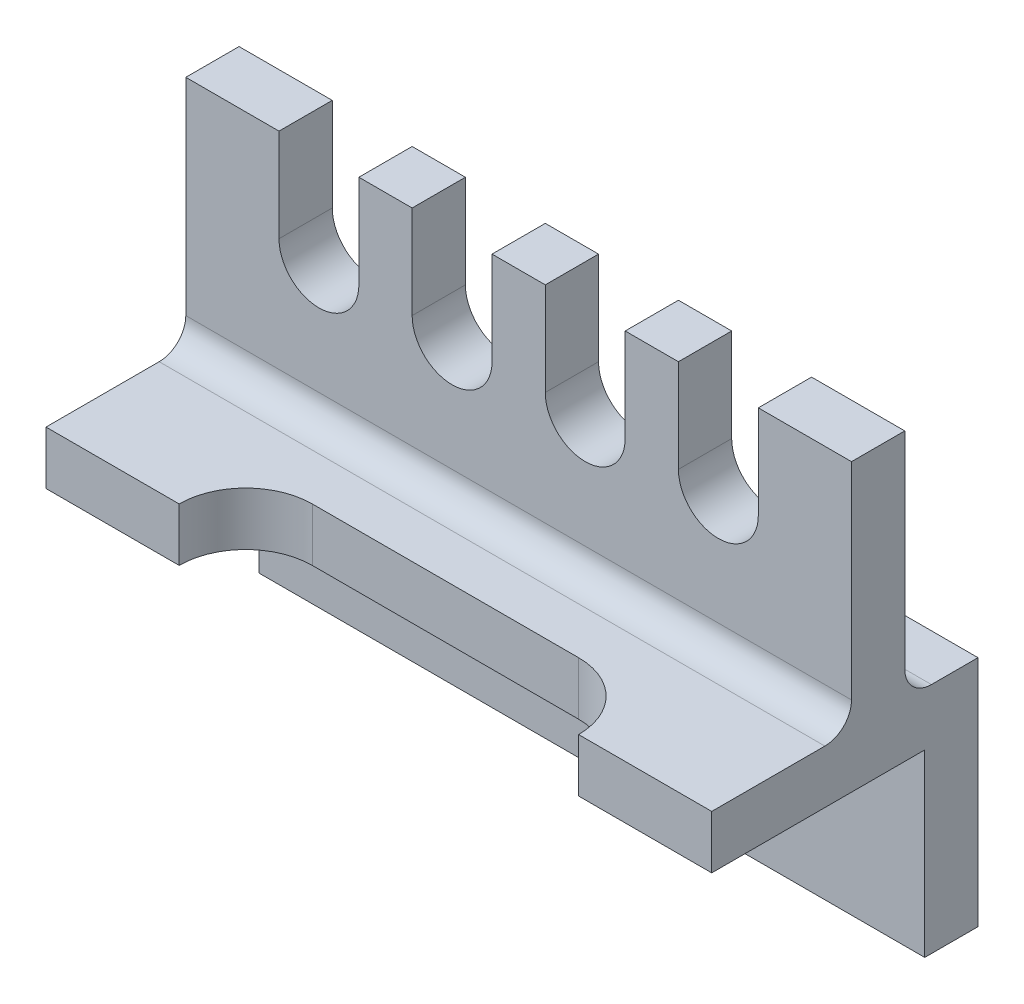
SolidWorks part; units mm, degrees
ref_plane "Front Plane" through (0, 0, 0) normal (0, 0, 1) x (1, 0, 0)
ref_plane "Top Plane" through (0, 0, 0) normal (0, 1, 0) x (1, 0, 0)
ref_plane "Right Plane" through (0, 0, 0) normal (1, 0, 0) x (0, 0, -1)
sketch "Sketch1" plane through (0, 0, 0) normal (1, 0, 0) x (0, 0, -1)
  line L0 (-19, 70) -> (-11, 70)
  line L1 (-11, 70) -> (-11, 39)
  line L2 (-7, 35) -> (0, 35)
  line L3 (0, 35) -> (0, 0)
  line L4 (0, 0) -> (-8, 0)
  line L5 (-8, 0) -> (-8, 27)
  line L6 (-8, 27) -> (-40, 27)
  line L7 (-40, 27) -> (-40, 35)
  line L8 (-40, 35) -> (-23, 35)
  line L9 (-19, 70) -> (-19, 39)
  arc A0 (-23, 35) -> (-19, 39) centre (-23, 39) ccw
  arc A1 (-11, 39) -> (-7, 35) centre (-7, 39) ccw
  point P8 (-3.4201, 43)
  point P10 (-40, 31)
  dimension "D8" = 8
  dimension "D1" = 8
  dimension "D2" = 70
  dimension "D3" = 35
  dimension "D4" = 8
  dimension "D5" = 8
  dimension "D6" = 40
  dimension "D7" = 21
extrude "Boss-Extrude2" add sketch "Sketch1" along normal blind 100
sketch "Sketch2" plane through (0, 0, 19) normal (0, 0, 1) x (1, 0, 0)
  line L0 (0, 70) -> (0, 39) construction
  line L1 (100, 70) -> (0, 70) construction
  line L2 (14, 56) -> (14, 70)
  line L3 (26, 56) -> (26, 70)
  line L4 (26, 70) -> (14, 70)
  line L5 (34, 56) -> (34, 70)
  line L6 (46, 56) -> (46, 70)
  line L7 (46, 70) -> (34, 70)
  line L8 (54, 56) -> (54, 70)
  line L9 (66, 56) -> (66, 70)
  line L10 (66, 70) -> (54, 70)
  line L11 (74, 56) -> (74, 70)
  line L12 (86, 56) -> (86, 70)
  line L13 (86, 70) -> (74, 70)
  arc A0 (14, 56) -> (26, 56) centre (20, 56) ccw
  arc A1 (34, 56) -> (46, 56) centre (40, 56) ccw
  arc A2 (54, 56) -> (66, 56) centre (60, 56) ccw
  arc A3 (74, 56) -> (86, 56) centre (80, 56) ccw
  point P27 (0, 0)
  point P28 (0, 0)
  point P29 (0, 0)
  dimension "D1" = 12
  dimension "D2" = 20
  dimension "D3" = 20
  dimension "D4" = 20
  dimension "D5" = 20
  dimension "D6" = 14
extrude "Cut-Extrude1" cut sketch "Sketch2" against normal up to next
sketch "Sketch3" plane through (0, 35, 0) normal (0, 1, 0) x (1, 0, 0)
  line L0 (20, -40) -> (80, -40)
  line L1 (100, -40) -> (0, -40) construction
  line L2 (0, -23) -> (0, -40) construction
  line L3 (30, -30) -> (70, -30)
  arc A1 (30, -30) -> (20, -40) centre (30, -40) ccw
  arc A2 (80, -40) -> (70, -30) centre (70, -40) ccw
  dimension "D1" = 20
  dimension "D3" = 40
  dimension "D2" = 30
extrude "Cut-Extrude2" cut sketch "Sketch3" against normal up to next
